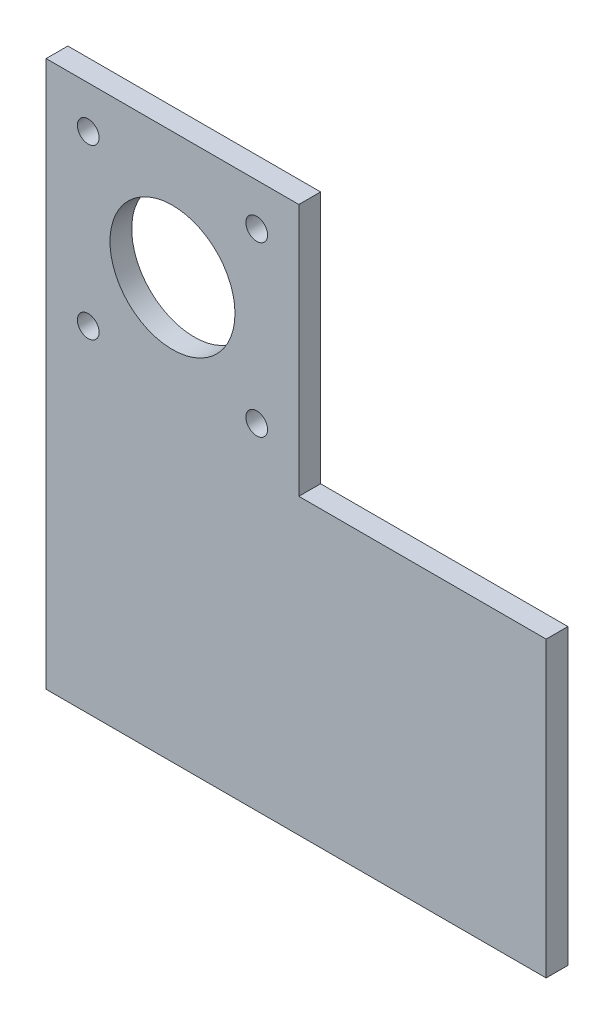
SolidWorks part; units mm, degrees
ref_plane "Front Plane" through (0, 0, 0) normal (0, 0, 1) x (1, 0, 0)
ref_plane "Top Plane" through (0, 0, 0) normal (0, 1, 0) x (1, 0, 0)
ref_plane "Right Plane" through (0, 0, 0) normal (1, 0, 0) x (0, 0, -1)
sketch "Sketch1" plane through (0, 0, 0) normal (0, 0, 1) x (1, 0, 0)
  line L0 (0, 0) -> (0, 100.5)
  line L1 (0, 100.5) -> (46.5, 100.5)
  line L2 (46.5, 100.5) -> (46.5, 54)
  line L3 (46.5, 54) -> (92, 54)
  line L4 (92, 54) -> (92, 0)
  line L5 (92, 0) -> (0, 0)
  line L6 (0, 100.5) -> (46.5, 54) construction
  line L7 (46.5, 100.5) -> (0.5027, 54.5027) construction
  circle A0 centre (23.25, 77.25) radius 11.5
  circle A1 centre (7.75, 92.75) radius 2
  circle A2 centre (38.75, 92.75) radius 2
  circle A3 centre (38.75, 61.75) radius 2
  circle A4 centre (7.75, 61.75) radius 2
  point P18 (-65.609, 62.8607)
  point P19 (-48.1308, 79.2524)
  dimension "D5" = 23
  dimension "D6" = 4
  dimension "D1" = 54
  dimension "D2" = 92
  dimension "D3" = 46.5
  dimension "D4" = 46.5
  dimension "D7" = 31
  dimension "D8" = 31
  dimension "D9" = 31
  dimension "D10" = 31
  dimension "D11" = 46
extrude "Boss-Extrude1" add sketch "Sketch1" along normal blind 4
